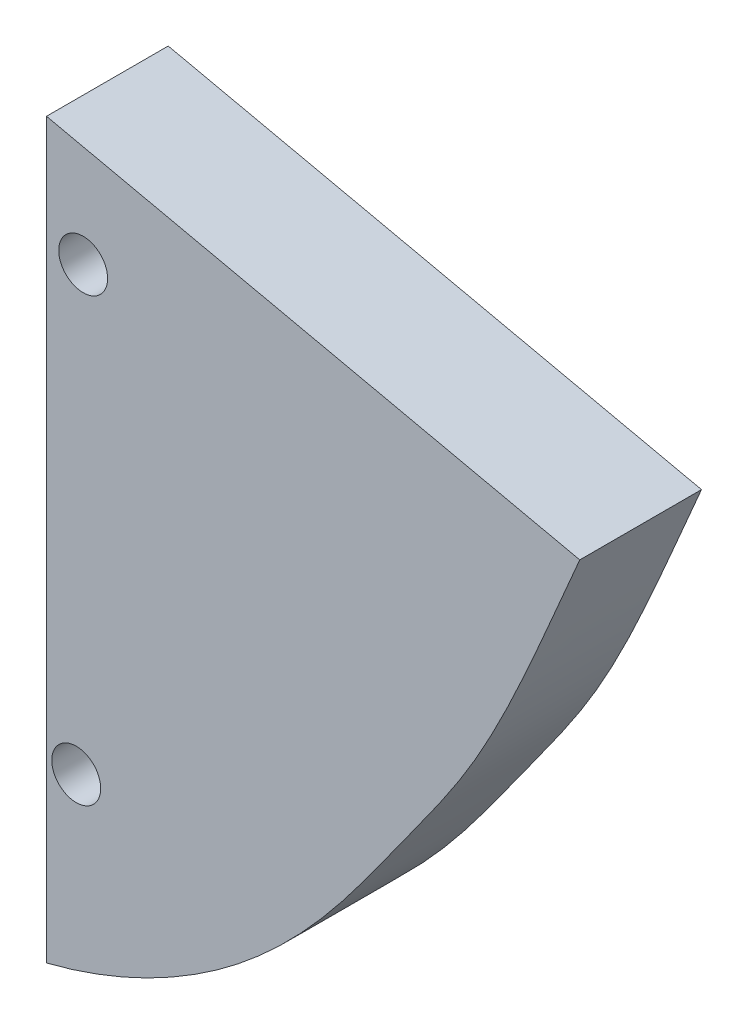
SolidWorks part; units mm, degrees
ref_plane "Alzado" through (0, 0, 0) normal (0, 0, 1) x (1, 0, 0)
ref_plane "Planta" through (0, 0, 0) normal (0, 1, 0) x (1, 0, 0)
ref_plane "Vista lateral" through (0, 0, 0) normal (1, 0, 0) x (0, 0, -1)
sketch "Croquis1" plane through (0, 0, 0) normal (0, 0, 1) x (1, 0, 0)
  line L1 (0, -4) -> (0, 26)
  line L2 (0, 26) -> (21.8169, 21.1914)
  spline S0 degree 3 poles (0, -4) (2.9068, -3.2679) (7.1894, -1.0919) (11.6437, 3.4608) (14.4738, 7.4808) (17.3378, 11.3693) (19.6481, 16.0329) (21.0177, 19.3556) (21.8169, 21.1914) knots 0 0 0 0 0.260018 0.407189 0.549306 0.687276 0.826057 1 1 1 1
  dimension "D1" = 26
  dimension "D2" = 30
extrude "Saliente-Extruir1" add sketch "Croquis1" along normal blind 4.98
sketch "Croquis2" plane through (0, 0, 4.98) normal (0, 0, 1) x (1, 0, 0)
  line L1 (0, 26) -> (0, -4) construction
  circle A0 centre (1.5, 21.5) radius 1
  dimension "D1" = 2
  dimension "D3" = 1.5
extrude "Cortar-Extruir1" cut sketch "Croquis2" against normal blind 5
sketch "Croquis4" plane through (0, 0, 4.98) normal (0, 0, 1) x (1, 0, 0)
  circle A0 centre (1.2167, 3.2911) radius 1
  dimension "D1" = 2
extrude "Cortar-Extruir3" cut sketch "Croquis4" against normal up to next
